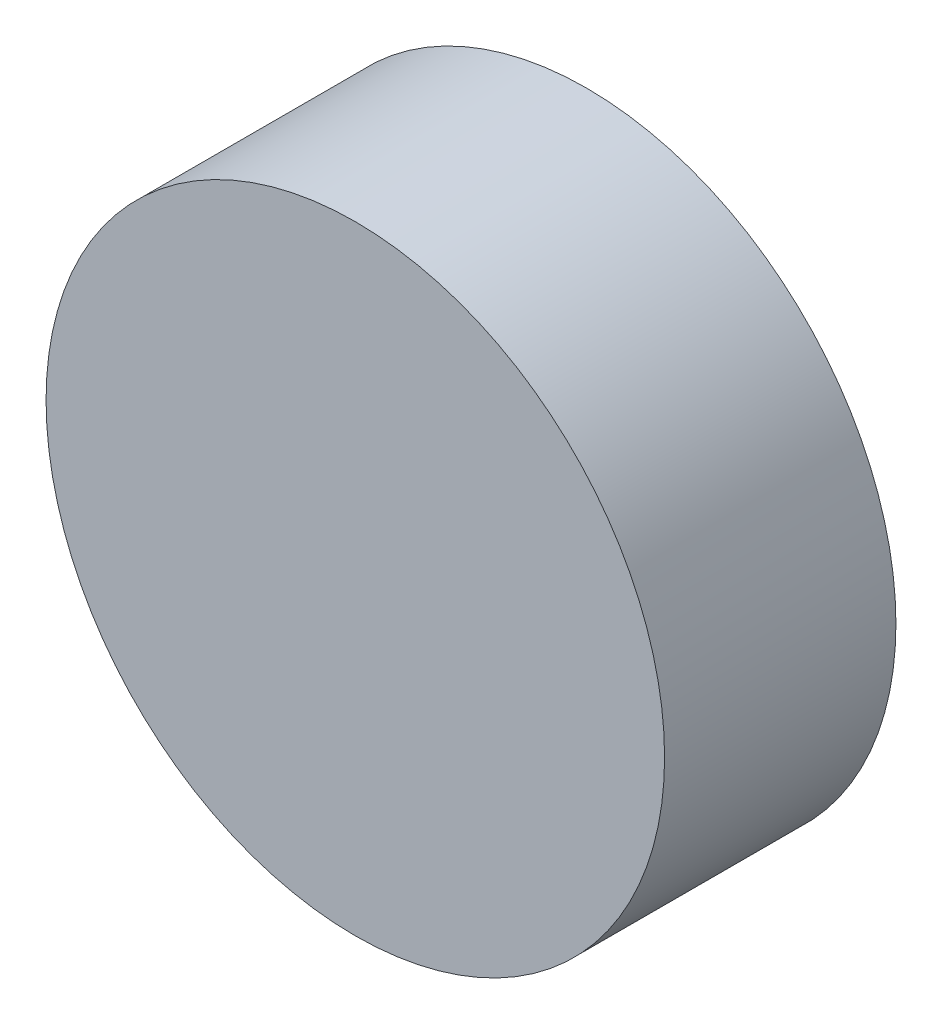
SolidWorks part; units mm, degrees
ref_plane "Front Plane" through (0, 0, 0) normal (0, 0, 1) x (1, 0, 0)
ref_plane "Top Plane" through (0, 0, 0) normal (0, 1, 0) x (1, 0, 0)
ref_plane "Right Plane" through (0, 0, 0) normal (1, 0, 0) x (0, 0, -1)
sketch "Sketch1" plane through (0, 0, 0) normal (0, 0, 1) x (1, 0, 0)
  circle A0 centre (0, 0) radius 6.35
  dimension "D1" = 12.7
extrude "Boss-Extrude1" add sketch "Sketch1" along normal blind 4.7498
